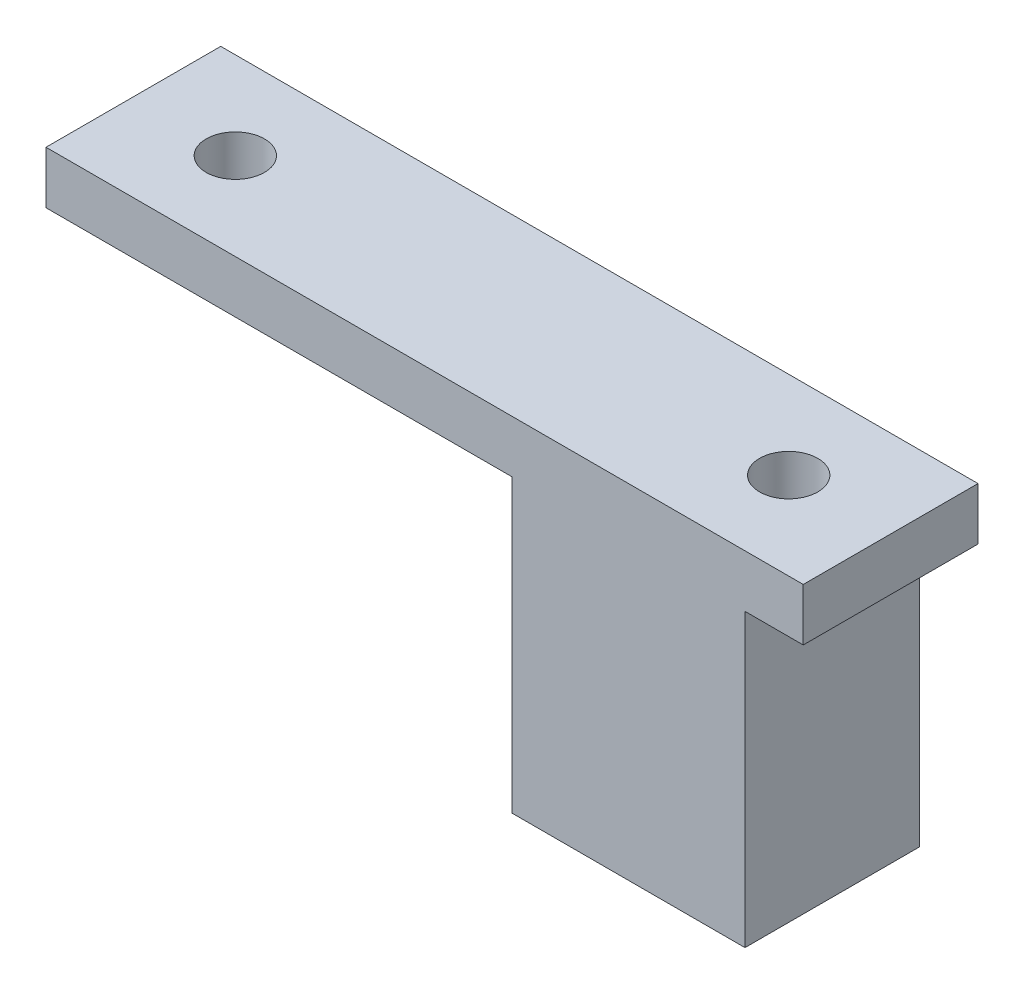
SolidWorks part; units mm, degrees
ref_plane "Front Plane" through (0, 0, 0) normal (0, 0, 1) x (1, 0, 0)
ref_plane "Top Plane" through (0, 0, 0) normal (0, 1, 0) x (1, 0, 0)
ref_plane "Right Plane" through (0, 0, 0) normal (1, 0, 0) x (0, 0, -1)
sketch "Sketch1" plane through (0, 0, 0) normal (0, 1, 0) x (1, 0, 0)
  line L1 (0, 0) -> (-8, 0)
  line L2 (0, 0) -> (0, 6)
  line L3 (0, 6) -> (-8, 6)
  line L4 (-8, 0) -> (-8, 6)
  dimension "D1" = 8
  dimension "D2" = 6
extrude "Boss-Extrude1" add sketch "Sketch1" along normal blind 10
sketch "Sketch3" plane through (0, 10, 0) normal (0, 1, 0) x (1, 0, 0)
  line L0 (-1.5, 3) -> (-1.4692, 3) construction
  line L1 (0, 6) -> (-8, 6) construction
  line L3 (-8, 3) -> (0, 3) construction
  line L4 (-8, 6) -> (-8, 0) construction
  line L5 (0, 0) -> (0, 6) construction
  line L7 (2, 0) -> (-24, 0)
  line L8 (2, 0) -> (2, 6)
  line L9 (2, 6) -> (-24, 6)
  line L10 (-24, 0) -> (-24, 6)
  line L11 (2, 0) -> (-24, 6) construction
  line L12 (2, 6) -> (-24, 0) construction
  circle A0 centre (-20.5, 3) radius 1
  circle A1 centre (-1.5, 3) radius 1
  point P3 (0, 0)
  point P4 (0, 0)
  point P5 (0, 0)
  point P12 (-11, 3)
  point P21 (0, 0)
  dimension "D3" = 2
  dimension "D7" = 2
  dimension "D9" = 1.5
  dimension "D1" = 26
  dimension "D2" = 6
  dimension "D4" = 3.5
  dimension "D5" = 3
  dimension "D6" = 19
  dimension "D8" = 3.5
extrude "Boss-Extrude2" add sketch "Sketch3" along normal blind 1.8
sketch "Sketch4" plane through (0, 0, 0) normal (0, -1, 0) x (1, 0, 0)
  line L0 (-4, 0) -> (-4, -6) construction
  line L1 (-8, 0) -> (0, 0) construction
  line L2 (0, -6) -> (-8, -6) construction
  line L4 (-1.05, -4.6) -> (-6.95, -4.6)
  line L5 (-1.05, -4.6) -> (-1.05, -1.4)
  line L6 (-1.05, -1.4) -> (-6.95, -1.4)
  line L7 (-6.95, -4.6) -> (-6.95, -1.4)
  line L8 (-1.05, -4.6) -> (-6.95, -1.4) construction
  line L9 (-1.05, -1.4) -> (-6.95, -4.6) construction
  point P6 (-4, -3)
  dimension "D1" = 5.9
  dimension "D2" = 3.2
extrude "Cut-Extrude1" cut sketch "Sketch4" against normal blind 7
sketch "Sketch6" plane through (0, 11.8, 0) normal (0, 1, 0) x (1, 0, 0)
  circle A0 centre (-1.5, 3) radius 1
extrude "Cut-Extrude2" cut sketch "Sketch6" against normal blind 4
